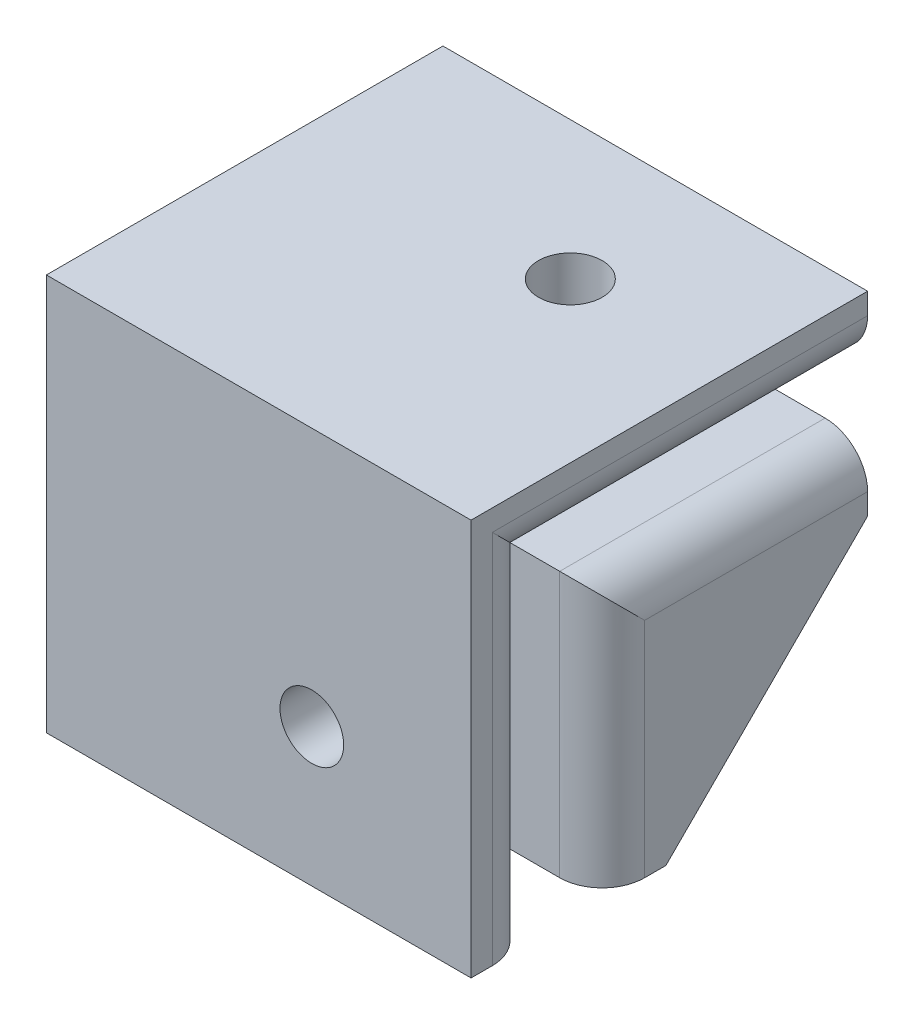
SolidWorks part; units mm, degrees
ref_plane "Front Plane" through (0, 0, 0) normal (0, 0, 1) x (1, 0, 0)
ref_plane "Top Plane" through (0, 0, 0) normal (0, 1, 0) x (1, 0, 0)
ref_plane "Right Plane" through (0, 0, 0) normal (1, 0, 0) x (0, 0, -1)
sketch "Sketch1" plane through (0, 0, 0) normal (1, 0, 0) x (0, 0, -1)
  line L0 (0, 0) -> (0, -12.5) construction
  line L1 (0, -12.5) -> (-3.175, -12.5)
  line L2 (-3.175, -12.5) -> (-3.175, 3.175) construction
  line L3 (-3.175, 3.175) -> (12.5, 3.175) construction
  line L4 (12.5, 3.175) -> (12.5, 0)
  line L5 (12.5, 0) -> (0, 0) construction
  line L6 (0, -12.5) -> (3, -12.5)
  line L7 (3, -12.5) -> (12.5, -3)
  line L8 (12.5, -3) -> (12.5, 0)
  line L9 (12.5, 3.175) -> (12.5, 6.175)
  line L10 (12.5, 6.175) -> (-6.175, 6.175)
  line L11 (-6.175, 6.175) -> (-6.175, -12.5)
  line L12 (-6.175, -12.5) -> (-3.175, -12.5)
  dimension "D1" = 3.175
  dimension "D2" = 3.175
  dimension "D3" = 12.5
  dimension "D4" = 12.5
  dimension "D5" = 3
  dimension "D6" = 3
  dimension "D7" = 3
  dimension "D8" = 3
extrude "Boss-Extrude1" add sketch "Sketch1" along normal blind 20
sketch "Sketch2" plane through (20, 0, 0) normal (1, 0, 0) x (0, 0, -1)
  line L0 (-3.175, -12.5) -> (0, -12.5)
  line L1 (0, -12.5) -> (0, 0)
  line L2 (0, 0) -> (12.5, 0)
  line L3 (12.5, 0) -> (12.5, 3.175)
  line L4 (12.5, 3.175) -> (-3.175, 3.175)
  line L5 (-3.175, 3.175) -> (-3.175, -12.5)
extrude "Cut-Extrude1" cut sketch "Sketch2" against normal blind 15
fillet "Fillet1" radius 2 4 edges at (20, -4.6625, 3.175) (20, -6.25, 0) (20, 0, -6.25) (20, 3.175, -4.6625)
sketch "Sketch3" plane through (0, 6.175, 0) normal (0, 1, 0) x (1, 0, 0)
  line L0 (5, 12.5) -> (5, -6.175) construction
  line L1 (20, 12.5) -> (0, 12.5) construction
  line L2 (20, -6.175) -> (0, -6.175) construction
  line L3 (0, 12.5) -> (0, -6.175) construction
  line L4 (5, 6) -> (20, 6) construction
  line L5 (5, -3.175) -> (20, -3.175) construction
  line L6 (20, 12.5) -> (20, -6.175) construction
  line L7 (5, 0) -> (20, 0) construction
  line L8 (5, 3) -> (20, 3) construction
  circle A0 centre (12.5, 6) radius 1.5
  dimension "D2" = 3
  dimension "D1" = 5
  dimension "D3" = 3
  dimension "D4" = 3.175
  dimension "D5" = 3
  dimension "D6" = 6
extrude "Cut-Extrude2" cut sketch "Sketch3" against normal through all
sketch "Sketch4" plane through (0, 0, 6.175) normal (0, 0, 1) x (1, 0, 0)
  line L0 (5, 6.175) -> (5, -12.5) construction
  line L1 (20, 6.175) -> (0, 6.175) construction
  line L2 (20, -12.5) -> (0, -12.5) construction
  line L3 (0, 6.175) -> (0, -12.5) construction
  line L4 (20, -6) -> (5, -6) construction
  circle A0 centre (12.5, -6) radius 1.5
  dimension "D2" = 3
  dimension "D1" = 5
  dimension "D3" = 12.175
extrude "Cut-Extrude3" cut sketch "Sketch4" against normal through all
scale "Scale1" scale about centroid uniform scaling yes scale factor 1.02
